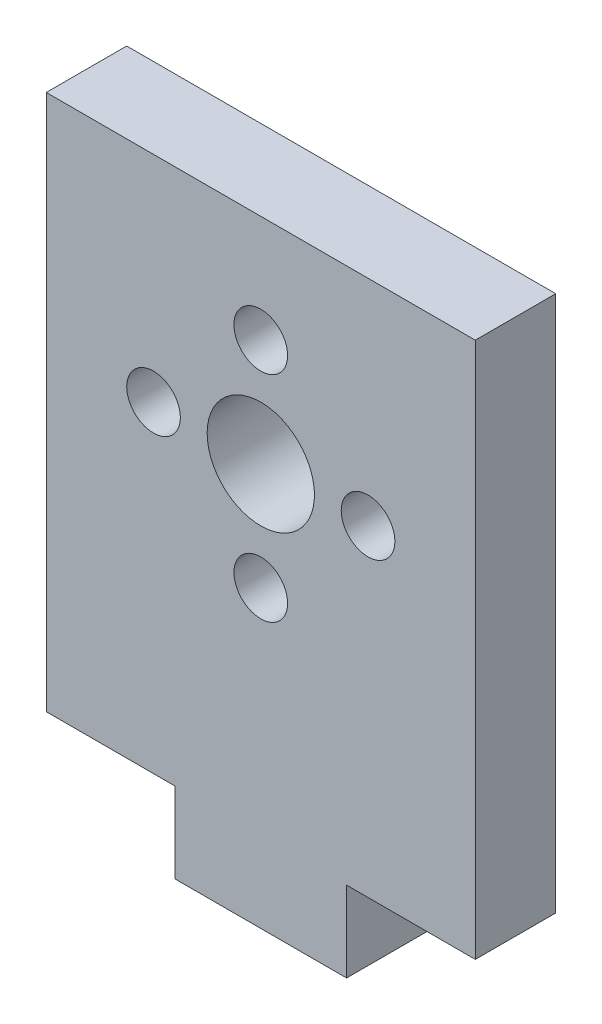
SolidWorks part; units mm, degrees
ref_plane "Front Plane" through (0, 0, 0) normal (0, 0, 1) x (1, 0, 0)
ref_plane "Top Plane" through (0, 0, 0) normal (0, 1, 0) x (1, 0, 0)
ref_plane "Right Plane" through (0, 0, 0) normal (1, 0, 0) x (0, 0, -1)
sketch "Sketch1" plane through (0, 0, 0) normal (0, 0, 1) x (1, 0, 0)
  line L3 (25.4, 0) -> (25.4, 31.75)
  line L4 (25.4, 31.75) -> (0, 31.75)
  line L5 (0, 31.75) -> (0, 0)
  line L8 (12.7, 19.05) -> (12.7, 25.4) construction
  line L9 (19.05, 19.05) -> (12.7, 19.05) construction
  line L10 (12.7, 12.7) -> (12.7, 19.05) construction
  line L11 (6.35, 19.05) -> (12.7, 19.05) construction
  line L12 (12.7, 25.4) -> (12.7, 31.75) construction
  line L13 (0, 0) -> (7.62, 0)
  line L14 (7.62, 0) -> (7.62, -4.7625)
  line L15 (7.62, -4.7625) -> (17.78, -4.7625)
  line L16 (17.78, -4.7625) -> (17.78, 0)
  line L17 (17.78, 0) -> (25.4, 0)
  circle A0 centre (12.7, 19.05) radius 3.175
  circle A1 centre (12.7, 25.4) radius 1.5875
  circle A2 centre (19.05, 19.05) radius 1.5875
  circle A3 centre (6.35, 19.05) radius 1.5875
  circle A4 centre (12.7, 12.7) radius 1.5875
  dimension "D2" = 3.175
  dimension "D3" = 6.35
  dimension "D1" = 10.16
  dimension "D4" = 4.7625
  dimension "D5" = 31.75
  dimension "D6" = 6.35
  dimension "D7" = 6.35
  dimension "D8" = 25.4
extrude "Boss-Extrude1" add sketch "Sketch1" along normal blind 4.7625
